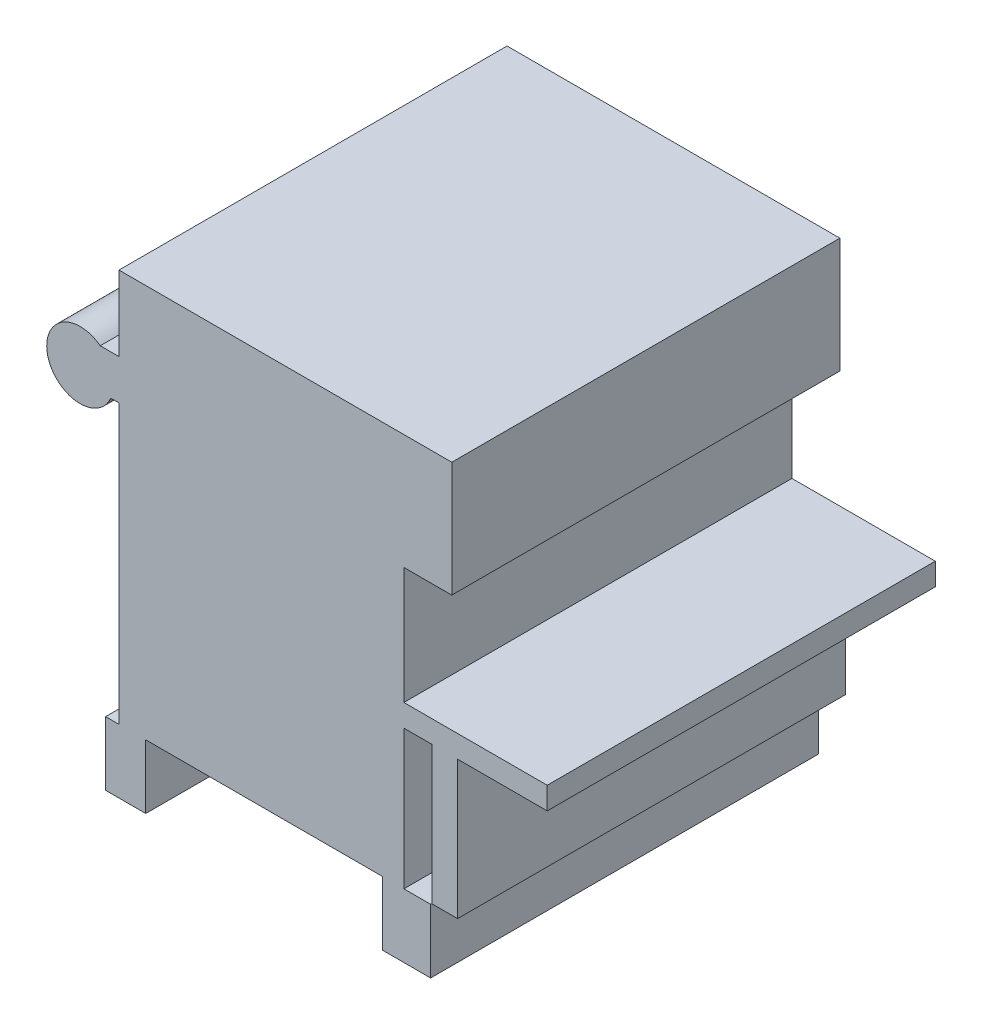
SolidWorks part; units mm, degrees
ref_plane "Front Plane" through (0, 0, 0) normal (0, 0, 1) x (1, 0, 0)
ref_plane "Top Plane" through (0, 0, 0) normal (0, 1, 0) x (1, 0, 0)
ref_plane "Right Plane" through (0, 0, 0) normal (1, 0, 0) x (0, 0, -1)
sketch "Sketch1" plane through (0, 0, 0) normal (0, 0, 1) x (1, 0, 0)
  line L0 (540.766, 306.324) -> (540.766, 528.32)
  line L1 (50.8, 0) -> (500.126, 0)
  line L2 (0, 0) -> (0, 528.32)
  line L4 (540.766, 0) -> (540.766, 264.16)
  line L5 (540.766, 528.32) -> (631.698, 528.32)
  line L8 (631.698, 528.32) -> (631.698, 550.164)
  line L10 (0, 604.52) -> (0, 746.76)
  line L11 (0, 746.76) -> (631.698, 746.76)
  line L12 (631.698, 550.164) -> (631.698, 746.76)
  line L17 (0, 0) -> (-25.4, 0)
  line L18 (50.8, 0) -> (50.8, -121.158)
  line L19 (50.8, -121.158) -> (-25.4, -121.158)
  line L20 (-25.4, 0) -> (-25.4, -121.158)
  line L21 (540.766, 0) -> (591.566, 0)
  line L22 (500.126, 0) -> (500.126, -121.158)
  line L23 (500.126, -121.158) -> (591.566, -121.158)
  line L24 (591.566, 0) -> (591.566, -121.158)
  line L25 (540.766, 264.16) -> (594.106, 264.16)
  line L27 (540.766, 306.324) -> (812.8, 306.324)
  line L28 (812.8, 264.16) -> (812.8, 306.324)
  line L30 (594.106, 264.16) -> (594.106, 2.032)
  line L31 (594.106, 2.032) -> (642.7044, 2.032)
  line L32 (642.7044, 264.16) -> (642.7044, 2.032)
  line L33 (0, 528.32) -> (-15.4613, 528.32)
  line L35 (0, 604.52) -> (-35.56, 604.52)
  line L37 (642.7044, 264.16) -> (812.8, 264.16)
  arc A1 (-35.56, 604.52) -> (-15.4613, 528.32) centre (-73.66, 553.72) ccw
  dimension "D19" = 127
  dimension "D1" = 121.158
  dimension "D2" = 76.2
  dimension "D3" = 25.4
  dimension "D4" = 91.44
  dimension "D5" = 121.158
  dimension "D6" = 50.8
  dimension "D7" = 540.766
  dimension "D8" = 262.128
  dimension "D9" = 42.164
  dimension "D10" = 272.034
  dimension "D11" = 48.5984
  dimension "D12" = 264.16
  dimension "D13" = 53.34
  dimension "D14" = 631.698
  dimension "D15" = 196.596
  dimension "D16" = 21.844
  dimension "D24" = 50.8
extrude "Boss-Extrude1" add sketch "Sketch1" along normal blind 736.6
